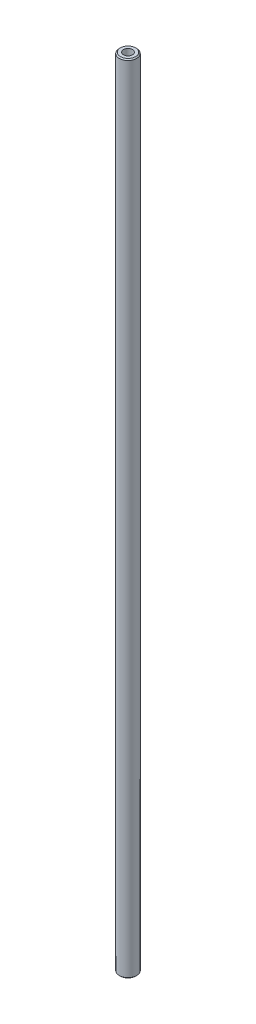
SolidWorks part; units mm, degrees
material "AISI 1020"
ref_plane "Plano frontal" through (0, 0, 0) normal (0, 0, 1) x (1, 0, 0)
ref_plane "Plano superior" through (0, 0, 0) normal (0, 1, 0) x (1, 0, 0)
ref_plane "Plano direito" through (0, 0, 0) normal (1, 0, 0) x (0, 0, -1)
sketch "Esboço3" plane through (0, 0, 0) normal (0, 1, 0) x (1, 0, 0)
  circle A0 centre (0, 0) radius 4
  dimension "D1" = 8
extrude "Ressalto-extrusão1" add sketch "Esboço3" along normal mid plane 367
chamfer "Chanfro1" distance 0.5 angle 45 2 edges at (0, -183.5, 4) (0, 183.5, 4)
hole_wizard "Furo roscado de M51" positions "Esboço5" profile "Esboço4" tap size "M5" standard "DIN"
sketch "Esboço5" plane through (0, 183.5, 0) normal (0, 1, 0) x (1, 0, 0)
  circle A0 centre (0, 0) radius 3.5 construction
  point P0 (0, 0)
sketch "Esboço4" plane through (0, 183.5, 0) normal (1, 0, 0) x (0, 0, 1)
  line L0 (0, 0) -> (0, 25.2618)
  line L1 (0, 25.2618) -> (2.1, 24)
  line L2 (2.1, 24) -> (2.1, 0)
  line L5 (2.1, 0) -> (0, 0)
  line L10 (0, 25.2618) -> (-2.1, 24) construction
  line L11 (0, -6.35) -> (0, 107.95) construction
  dimension "Tap Drill Dia." = 4.2
  dimension "Tap Drill Depth" = 24
  dimension "Drill Angle" = 118
cosmetic thread "Rosca de furo1" parameters "D1"=12, "D2"=5
mirror "Espelhar1" about plane through (0, 0, 0) normal (0, 1, 0) of "Furo roscado de M51"
